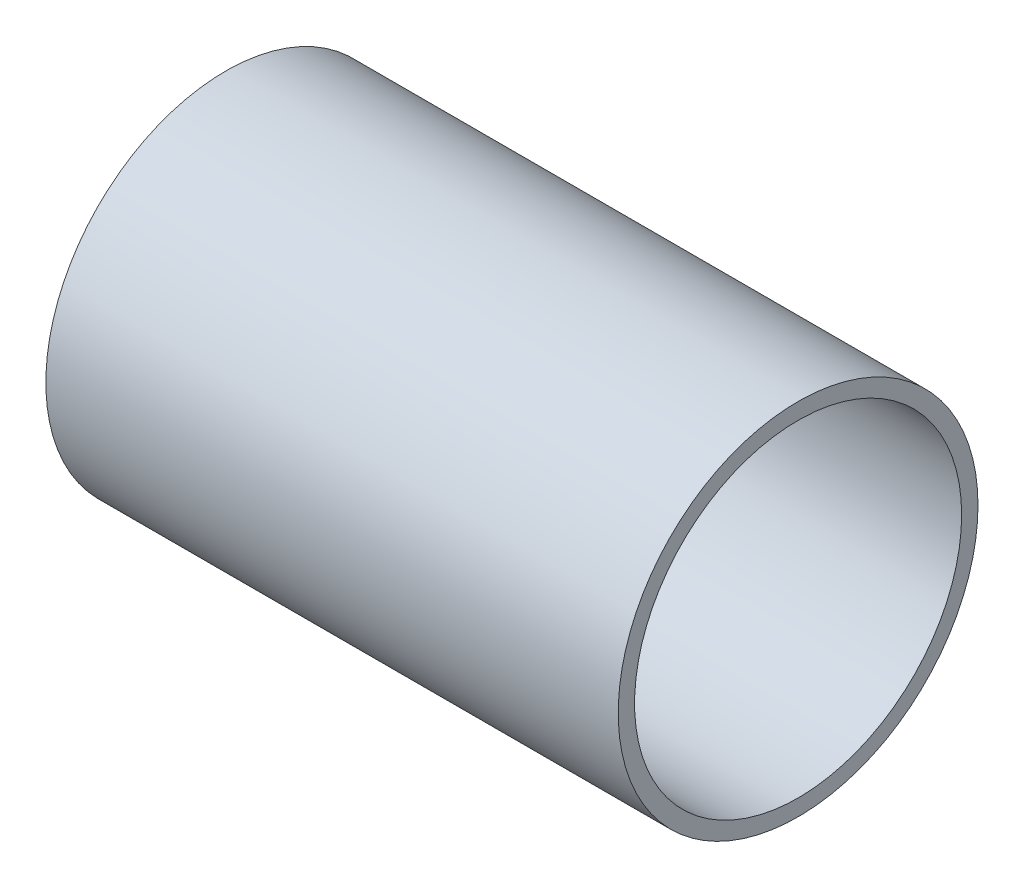
SolidWorks part; units mm, degrees
ref_plane "Front Plane" through (0, 0, 0) normal (0, 0, 1) x (1, 0, 0)
ref_plane "Top Plane" through (0, 0, 0) normal (0, 1, 0) x (1, 0, 0)
ref_plane "Right Plane" through (0, 0, 0) normal (1, 0, 0) x (0, 0, -1)
sketch "Sketch1" plane through (0, 0, 0) normal (1, 0, 0) x (0, 0, -1)
  circle A0 centre (0, 0) radius 22
  circle A1 centre (0, 0) radius 20
  dimension "D1" = 44
  dimension "D2" = 40
extrude "Boss-Extrude1" add sketch "Sketch1" along normal blind 70
